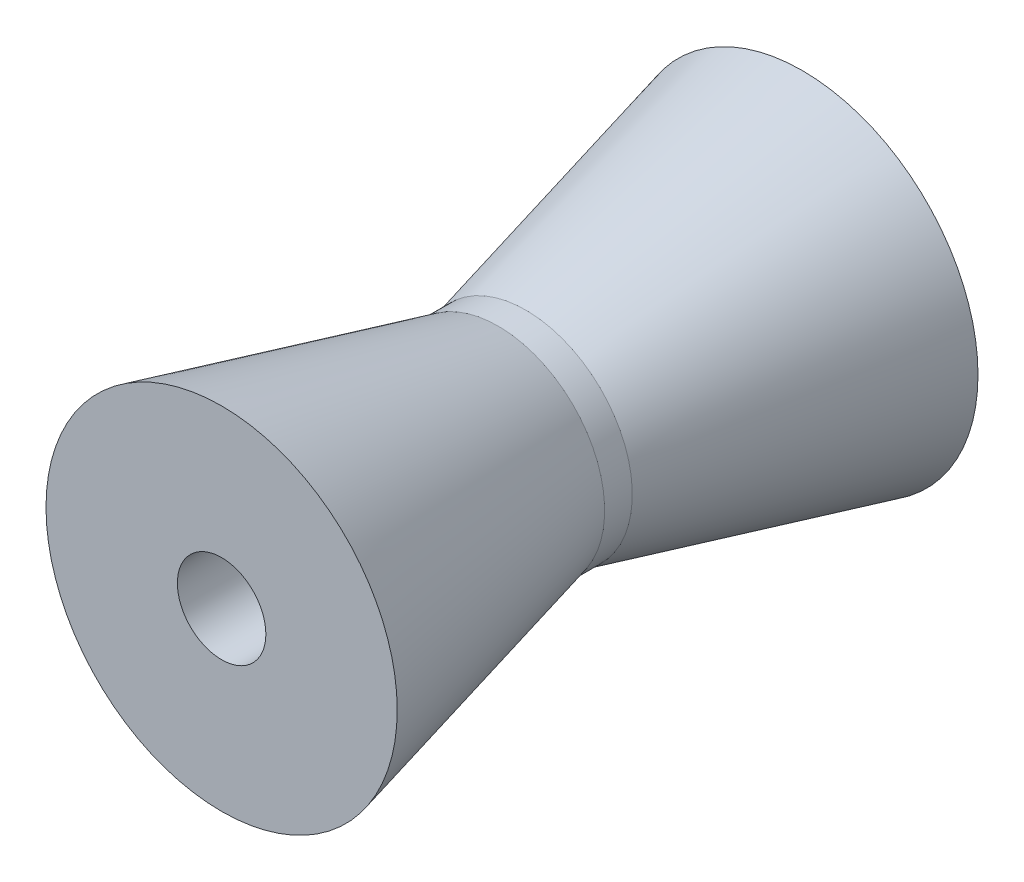
SolidWorks part; units mm, degrees
ref_plane "Plan de face" through (0, 0, 0) normal (0, 0, 1) x (1, 0, 0)
ref_plane "Plan de dessus" through (0, 0, 0) normal (0, 1, 0) x (1, 0, 0)
ref_plane "Plan de droite" through (0, 0, 0) normal (1, 0, 0) x (0, 0, -1)
sketch "Esquisse1" plane through (0, 0, 0) normal (0, 0, 1) x (1, 0, 0)
  circle A1 centre (0, 0) radius 2.032
  circle A2 centre (0, 0) radius 4.8895
  dimension "D1" = 4.064
  dimension "D2" = 2.8575
extrude "Boss.-Extru.1" add sketch "Esquisse1" along normal mid plane 26.67
sketch "Esquisse2" plane through (0, 0, 0) normal (1, 0, 0) x (0, 0, -1)
  line L0 (-0.635, 4.8895) -> (-13.335, 8.0645)
  line L1 (13.335, 4.8895) -> (-13.335, 4.8895) construction
  line L2 (-13.335, 8.0645) -> (-13.335, 4.8895)
  line L3 (-13.335, 4.8895) -> (-0.635, 4.8895)
  line L4 (0, 0) -> (-15.875, 0) construction
  dimension "D1" = 3.175
  dimension "D2" = 12.7
revolve "Révolution1" add sketch "Esquisse2" angle 360 about L4
mirror "Symétrie1" about plane through (0, 0, 0) normal (0, 0, 1) of "Révolution1"
